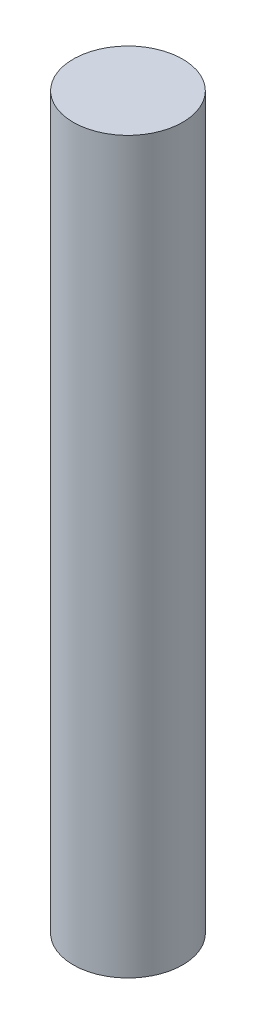
SolidWorks part; units mm, degrees
ref_plane "前基準面" through (0, 0, 0) normal (0, 0, 1) x (1, 0, 0)
ref_plane "上基準面" through (0, 0, 0) normal (0, 1, 0) x (1, 0, 0)
ref_plane "右基準面" through (0, 0, 0) normal (1, 0, 0) x (0, 0, -1)
sketch "草圖1" plane through (0, 0, 0) normal (0, 1, 0) x (1, 0, 0)
  circle A1 centre (0, 0) radius 1.5
  dimension "D1" = 3
extrude "填料-伸長1" add sketch "草圖1" along normal blind 20
